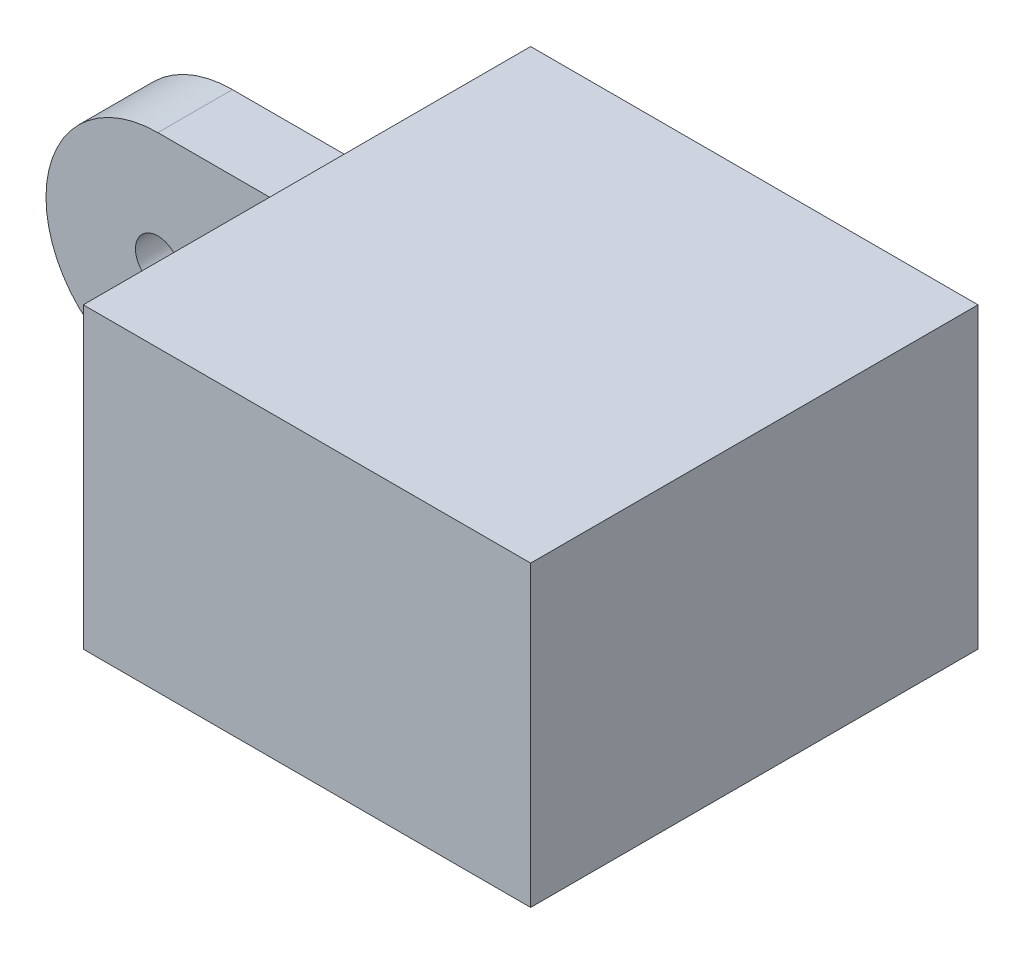
SolidWorks part; units mm, degrees
ref_plane "Front Plane" through (0, 0, 0) normal (0, 0, 1) x (1, 0, 0)
ref_plane "Top Plane" through (0, 0, 0) normal (0, 1, 0) x (1, 0, 0)
ref_plane "Right Plane" through (0, 0, 0) normal (1, 0, 0) x (0, 0, -1)
sketch "Sketch1" plane through (0, 0, 0) normal (0, 0, 1) x (1, 0, 0)
  line L0 (-30, -15) -> (-30, -20)
  line L1 (-30, 20) -> (30, 20)
  line L2 (-30, 20) -> (-30, 15)
  line L3 (-30, -20) -> (30, -20)
  line L4 (30, 20) -> (30, -20)
  line L5 (-30, 20) -> (30, -20) construction
  line L6 (-30, -20) -> (30, 20) construction
  line L7 (-50, 15) -> (-30, 15)
  line L8 (-50, -15) -> (-30, -15)
  arc A0 (-50, 15) -> (-50, -15) centre (-50, 0) ccw
  circle A1 centre (-50, 0) radius 3
  point P0 (0, 0)
  dimension "D3" = 30
  dimension "D4" = 6
  dimension "D1" = 40
  dimension "D2" = 60
extrude "Boss-Extrude1" add sketch "Sketch1" along normal blind 10
sketch "Sketch2" plane through (0, 0, 10) normal (0, 0, 1) x (1, 0, 0)
  line L0 (-30, 20) -> (-30, -20)
  line L1 (-30, -20) -> (30, -20)
  line L2 (30, -20) -> (30, 20)
  line L3 (30, 20) -> (-30, 20)
extrude "Boss-Extrude2" add sketch "Sketch2" along normal blind 30
sketch "Sketch3" plane through (0, 0, 0) normal (0, 0, -1) x (-1, 0, 0)
  line L0 (-30, 20) -> (-30, -20)
  line L1 (-30, -20) -> (30, -20)
  line L2 (30, -20) -> (30, 20)
  line L3 (30, 20) -> (-30, 20)
extrude "Boss-Extrude3" add sketch "Sketch3" along normal blind 20
